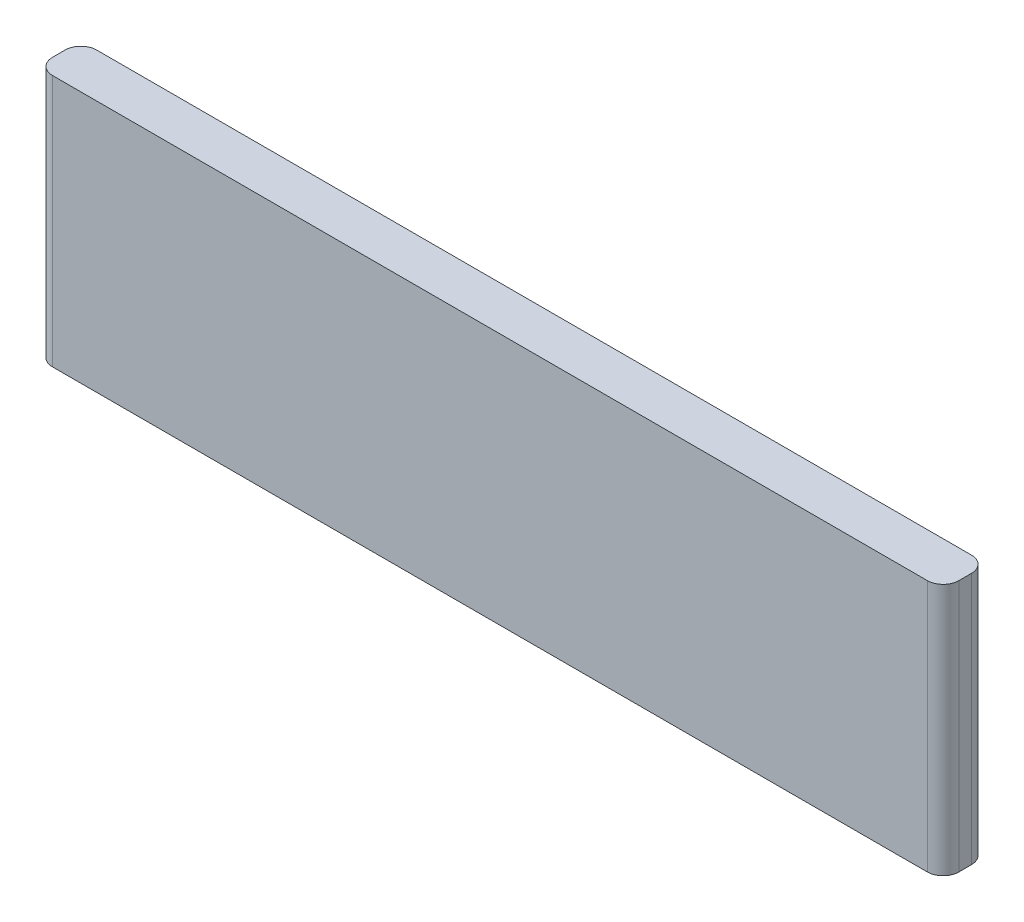
SolidWorks part; units mm, degrees
ref_plane "Front Plane" through (0, 0, 0) normal (0, 0, 1) x (1, 0, 0)
ref_plane "Top Plane" through (0, 0, 0) normal (0, 1, 0) x (1, 0, 0)
ref_plane "Right Plane" through (0, 0, 0) normal (1, 0, 0) x (0, 0, -1)
sketch "Sketch2" plane through (0, 0, 0) normal (0, 1, 0) x (1, 0, 0)
  line L1 (-21.55, -1.05) -> (21.55, -1.05)
  line L2 (-21.55, -1.05) -> (-21.55, 1.05)
  line L3 (-21.55, 1.05) -> (21.55, 1.05)
  line L4 (21.55, -1.05) -> (21.55, 1.05)
  line L5 (-21.55, -1.05) -> (21.55, 1.05) construction
  line L6 (-21.55, 1.05) -> (21.55, -1.05) construction
  point P0 (0, 0)
  dimension "D1" = 43.1
  dimension "D2" = 2.1
extrude "Boss-Extrude1" add sketch "Sketch2" along normal blind 12
fillet "Fillet1" radius 0.75 4 edges at (-21.55, 6, 1.05) (-21.55, 6, -1.05) (21.55, 6, -1.05) (21.55, 6, 1.05)
